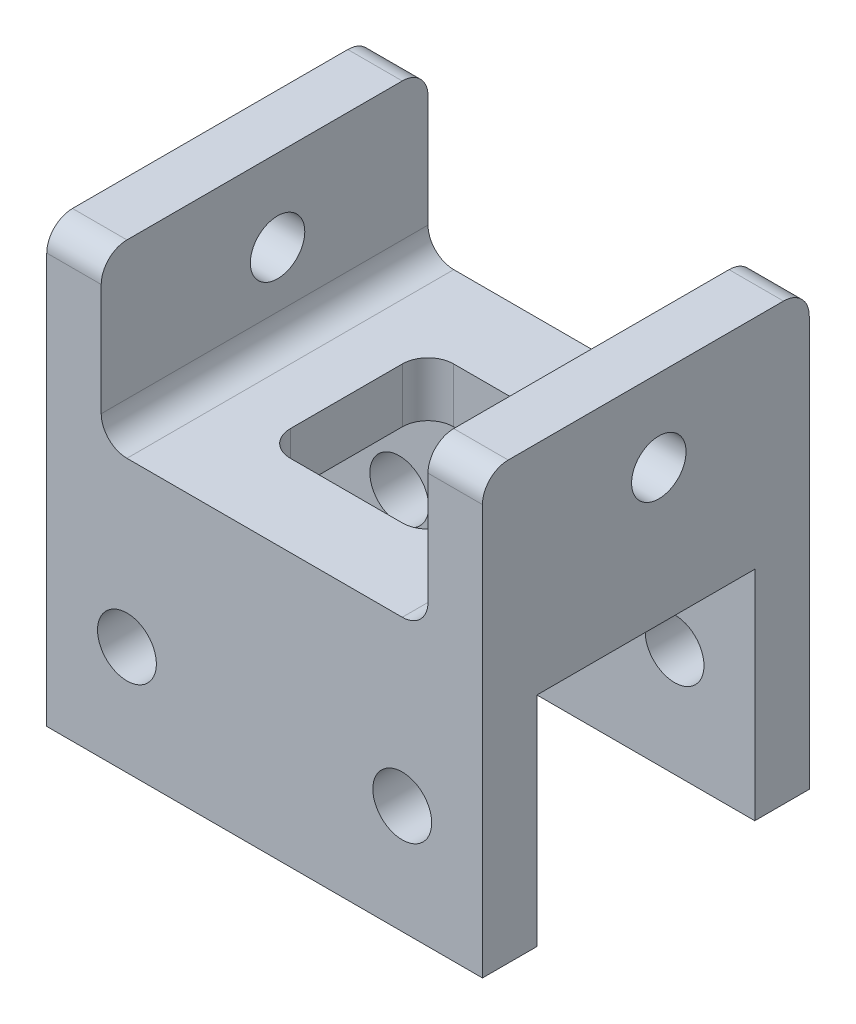
SolidWorks part; units mm, degrees
ref_plane "Front Plane" through (0, 0, 0) normal (0, 0, 1) x (1, 0, 0)
ref_plane "Top Plane" through (0, 0, 0) normal (0, 1, 0) x (1, 0, 0)
ref_plane "Right Plane" through (0, 0, 0) normal (1, 0, 0) x (0, 0, -1)
sketch "Sketch1" plane through (0, 0, 0) normal (0, 1, 0) x (1, 0, 0)
  line L1 (-109.7405, 60.0061) -> (-58.9405, 60.0061)
  line L2 (-109.7405, 60.0061) -> (-109.7405, 21.9061)
  line L3 (-109.7405, 21.9061) -> (-58.9405, 21.9061)
  line L4 (-58.9405, 60.0061) -> (-58.9405, 21.9061)
  line L5 (-109.7405, 60.0061) -> (-58.9405, 21.9061) construction
  line L6 (-109.7405, 21.9061) -> (-58.9405, 60.0061) construction
  point P0 (-84.3405, 40.9561)
  dimension "D1" = 50.8
  dimension "D2" = 38.1
extrude "Boss-Extrude1" add sketch "Sketch1" along normal blind 31.75
sketch "Sketch2" plane through (-58.9405, 0, 0) normal (1, 0, 0) x (0, 0, -1)
  line L0 (40.9561, 31.75) -> (40.9561, 0) construction
  line L1 (21.9061, 31.75) -> (60.0061, 31.75) construction
  line L2 (21.9061, 0) -> (60.0061, 0) construction
  line L3 (21.9061, 25.4) -> (60.0061, 25.4) construction
  line L4 (21.9061, 31.75) -> (21.9061, 0) construction
  line L5 (60.0061, 31.75) -> (60.0061, 0) construction
  line L7 (28.2561, 25.4) -> (53.6561, 25.4)
  line L8 (28.2561, 25.4) -> (28.2561, 0)
  line L9 (28.2561, 0) -> (53.6561, 0)
  line L10 (53.6561, 25.4) -> (53.6561, 0)
  dimension "D1" = 6.35
  dimension "D2" = 6.35
  dimension "D3" = 6.35
  dimension "D4" = 25.4
extrude "Cut-Extrude1" cut sketch "Sketch2" against normal through all
sketch "Sketch3" plane through (0, 31.75, 0) normal (0, 1, 0) x (1, 0, 0)
  line L0 (-58.9405, 60.0061) -> (-109.7405, 60.0061) construction
  line L1 (-103.3905, 60.0061) -> (-109.7405, 60.0061)
  line L2 (-103.3905, 60.0061) -> (-103.3905, 21.9061)
  line L3 (-103.3905, 21.9061) -> (-109.7405, 21.9061)
  line L4 (-109.7405, 60.0061) -> (-109.7405, 21.9061)
  dimension "D1" = 6.35
extrude "Boss-Extrude2" add sketch "Sketch3" along normal blind 19.05
sketch "Sketch4" plane through (0, 31.75, 0) normal (0, 1, 0) x (1, 0, 0)
  line L0 (-103.3905, 21.9061) -> (-58.9405, 21.9061) construction
  line L1 (-58.9405, 60.0061) -> (-65.2905, 60.0061)
  line L2 (-58.9405, 60.0061) -> (-58.9405, 21.9061)
  line L3 (-58.9405, 21.9061) -> (-65.2905, 21.9061)
  line L4 (-65.2905, 60.0061) -> (-65.2905, 21.9061)
  dimension "D1" = 6.35
extrude "Boss-Extrude3" add sketch "Sketch4" along normal blind 19.05
sketch "Sketch5" plane through (-103.3905, 0, 0) normal (1, 0, 0) x (0, 0, -1)
  line L0 (43.975, 31.75) -> (40.9561, 50.8) construction
  line L1 (21.9061, 31.75) -> (60.0061, 31.75) construction
  line L2 (21.9061, 50.8) -> (60.0061, 50.8) construction
  line L3 (21.9061, 41.275) -> (60.0061, 41.275) construction
  line L4 (21.9061, 50.8) -> (21.9061, 31.75) construction
  line L5 (60.0061, 50.8) -> (60.0061, 31.75) construction
  circle A0 centre (42.4656, 41.275) radius 3.175
extrude "Cut-Extrude2" cut sketch "Sketch5" against normal through all and the other way through all
fillet "Fillet1" radius 3 6 edges at (-106.5655, 50.8, -60.0061) (-106.5655, 50.8, -21.9061) (-62.1155, 50.8, -21.9061) (-62.1155, 50.8, -60.0061) (-65.2905, 31.75, -40.9561)
sketch "Sketch6" plane through (0, 0, -60.0061) normal (0, 0, -1) x (-1, 0, 0)
  line L0 (58.9405, 12.7) -> (109.7405, 12.7) construction
  line L1 (58.9405, 47.8) -> (58.9405, 0) construction
  line L2 (109.7405, 47.8) -> (109.7405, 0) construction
  line L3 (68.2905, 31.75) -> (68.2905, 0) construction
  line L4 (58.9405, 0) -> (109.7405, 0) construction
  line L5 (100.3905, 31.75) -> (100.3905, 0) construction
  circle A0 centre (68.2905, 12.7) radius 3.429
  dimension "D1" = 12.7
extrude "Cut-Extrude3" cut sketch "Sketch6" against normal through all
sketch "Sketch7" plane through (0, 0, -60.0061) normal (0, 0, -1) x (-1, 0, 0)
  line L0 (100.3905, 31.75) -> (100.3905, 0) construction
  line L1 (58.9405, 0) -> (109.7405, 0) construction
  line L2 (71.7195, 12.7) -> (109.7405, 12.7) construction
  line L3 (109.7405, 47.8) -> (109.7405, 0) construction
  circle A0 centre (68.2905, 12.7) radius 3.429 construction
  circle A1 centre (100.3905, 12.7) radius 3.429
extrude "Cut-Extrude4" cut sketch "Sketch7" against normal through all
sketch "Sketch8" plane through (0, 31.75, 0) normal (0, 1, 0) x (1, 0, 0)
  line L0 (-84.3405, 60.0061) -> (-84.3405, 21.9061) construction
  line L1 (-68.2905, 60.0061) -> (-100.3905, 60.0061) construction
  line L2 (-100.3905, 21.9061) -> (-68.2905, 21.9061) construction
  line L4 (-74.8155, 31.4311) -> (-93.8655, 31.4311)
  line L5 (-74.8155, 31.4311) -> (-74.8155, 50.4811)
  line L6 (-74.8155, 50.4811) -> (-93.8655, 50.4811)
  line L7 (-93.8655, 31.4311) -> (-93.8655, 50.4811)
  line L8 (-74.8155, 31.4311) -> (-93.8655, 50.4811) construction
  line L9 (-74.8155, 50.4811) -> (-93.8655, 31.4311) construction
  point P6 (-84.3405, 40.9561)
  dimension "D1" = 19.05
  dimension "D2" = 19.05
extrude "Cut-Extrude5" cut sketch "Sketch8" against normal through all
fillet "Fillet2" radius 3 2 edges at (-93.8655, 28.575, -50.4811) (-93.8655, 28.575, -31.4311)
fillet "Fillet3" radius 3 2 edges at (-74.8155, 28.575, -31.4311) (-74.8155, 28.575, -50.4811)
